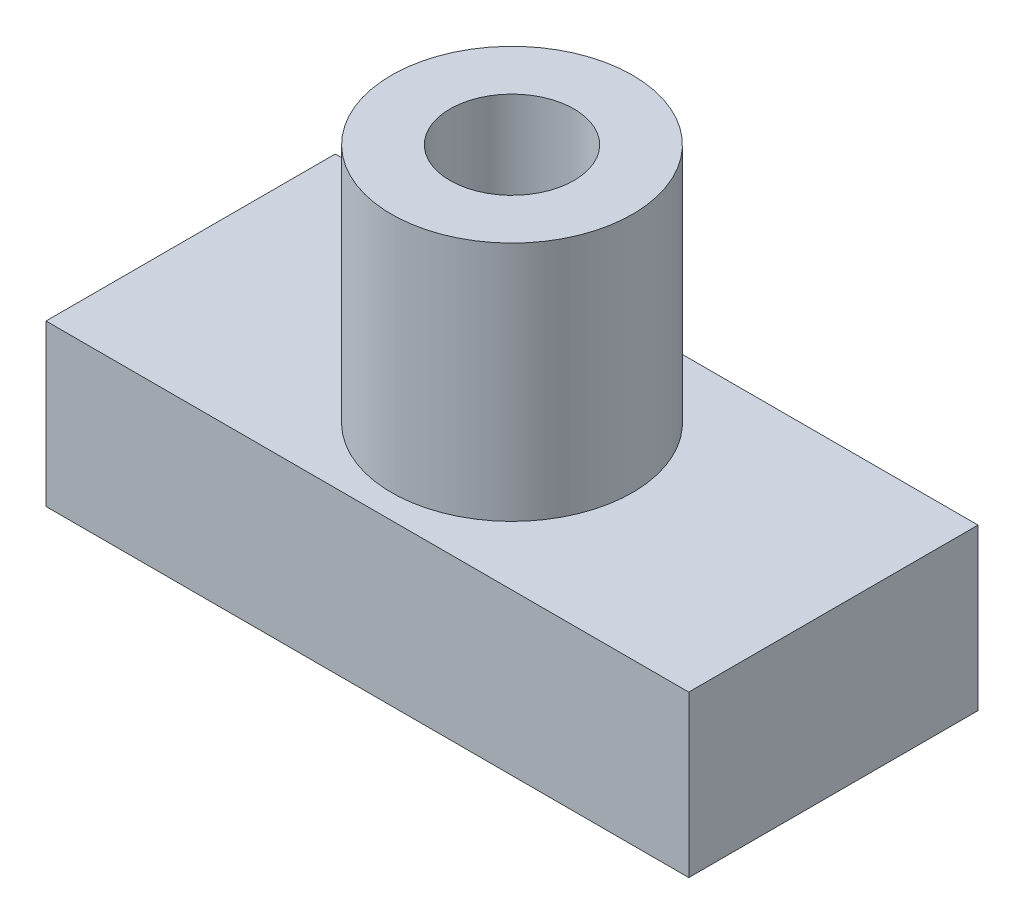
SolidWorks part; units mm, degrees
ref_plane "Front Plane" through (0, 0, 0) normal (0, 0, 1) x (1, 0, 0)
ref_plane "Top Plane" through (0, 0, 0) normal (0, 1, 0) x (1, 0, 0)
ref_plane "Right Plane" through (0, 0, 0) normal (1, 0, 0) x (0, 0, -1)
sketch "Sketch1" plane through (0, 0, 0) normal (0, 1, 0) x (1, 0, 0)
  line L1 (0, 0) -> (25.4, 0)
  line L2 (0, 0) -> (0, 11.43)
  line L3 (0, 11.43) -> (25.4, 11.43)
  line L4 (25.4, 0) -> (25.4, 11.43)
  dimension "D1" = 25.4
  dimension "D2" = 11.43
extrude "Boss-Extrude1" add sketch "Sketch1" along normal blind 6.35
sketch "Sketch2" plane through (0, 6.35, 0) normal (0, 1, 0) x (1, 0, 0)
  line L0 (0, 0) -> (25.4, 11.43) construction
  circle A0 centre (12.7, 5.715) radius 4.7625
  dimension "D1" = 9.525
extrude "Boss-Extrude2" add sketch "Sketch2" along normal blind 9.525
sketch "Sketch3" plane through (0, 15.875, 0) normal (0, 1, 0) x (1, 0, 0)
  circle A0 centre (12.7, 5.715) radius 2.4511
  dimension "D1" = 4.9022
extrude "Cut-Extrude1" cut sketch "Sketch3" against normal through all contours A0
hole_wizard "#60 (0.04) Diameter Hole1" positions "3DSketch5" profile "Sketch6" hole size "#60" standard "ANSI Inch"
sketch3d "3DSketch5"
  line L1 (12.7, 0, -11.43) -> (12.7, 0, -5.715) construction
  line L2 (25.4, 0, -11.43) -> (0, 0, -11.43) construction
  line L3 (12.7, 0, -5.715) -> (12.7, 15.875, -5.715) construction
  line L5 (8.89, 0, -1.905) -> (16.51, 0, -1.905) construction
  line L6 (8.89, 0, -1.905) -> (8.89, 0, -9.525) construction
  line L7 (16.51, 0, -1.905) -> (16.51, 0, -9.525) construction
  line L8 (8.89, 0, -9.525) -> (16.51, 0, -9.525) construction
  line L9 (8.89, 0, -9.525) -> (16.51, 0, -1.905) construction
  line L11 (8.89, 0, -1.905) -> (16.51, 0, -9.525) construction
  point P0 (8.89, 0, -1.905)
  point P2 (8.89, 0, -9.525)
  point P4 (16.51, 0, -9.525)
  point P6 (16.51, 0, -1.905)
  point P505 (26.7809, 0, -5.5717)
  point P507 (26.3296, 0, -5.2265)
  point P509 (26.1628, 0, -5.5347)
  point P511 (26.1628, 0, -5.5347)
  dimension "D1" = 7.62
  dimension "D2" = 7.62
sketch "Sketch6" plane through (8.89, 0, -1.905) normal (1, 0, 0) x (0, 0, -1)
  line L0 (0, 0) -> (0, 4.8234)
  line L1 (0, 4.8234) -> (1.4224, 3.9688)
  line L2 (1.4224, 3.9688) -> (1.4224, 0)
  line L5 (1.4224, 0) -> (0, 0)
  line L10 (0, 4.8234) -> (-1.4224, 3.9687) construction
  line L11 (0, -6.35) -> (0, 107.95) construction
  dimension "Hole Dia." = 2.8448
  dimension "Hole Depth" = 3.9688
  dimension "Drill Angle" = 118
